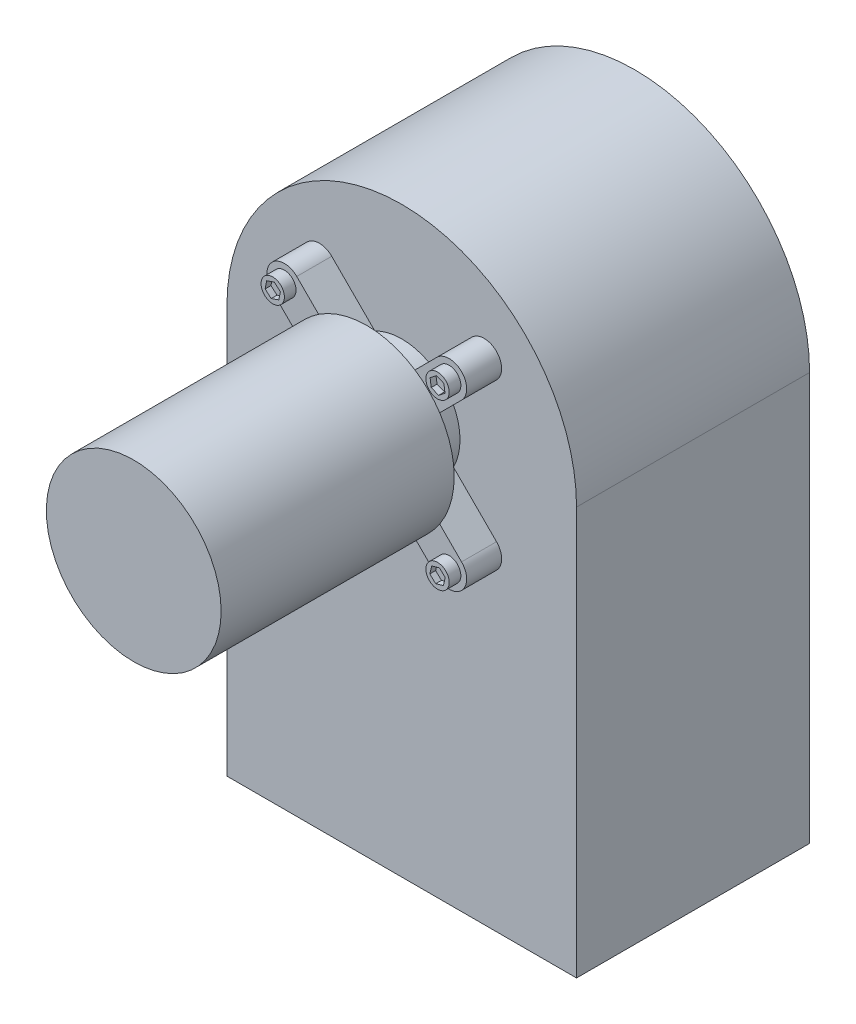
SolidWorks part; units mm, degrees
ref_plane "Front Plane" through (0, 0, 0) normal (0, 0, 1) x (1, 0, 0)
ref_plane "Top Plane" through (0, 0, 0) normal (0, 1, 0) x (1, 0, 0)
ref_plane "Right Plane" through (0, 0, 0) normal (1, 0, 0) x (0, 0, -1)
sketch "Sketch1" plane through (0, 0, 0) normal (0, 0, 1) x (1, 0, 0)
  line L1 (-15, 0) -> (15, 0)
  line L2 (-15, 0) -> (-15, -35)
  line L3 (-15, -35) -> (15, -35)
  line L4 (15, 0) -> (15, -35)
  line L5 (-15, 0) -> (15, -35) construction
  line L6 (-15, -35) -> (15, 0) construction
  circle A0 centre (0, 0) radius 15
  point P2 (0, -17.5)
  dimension "D1" = 30
  dimension "D2" = 35
extrude "Boss-Extrude1" add sketch "Sketch1" along normal blind 20 contours L1 A0 | L1 A0 | A0 L2 L3 L4
sketch "Sketch2" plane through (0, 0, 20) normal (0, 0, 1) x (1, 0, 0)
  circle A0 centre (0, 0) radius 4
  arc A1 (15, 0) -> (-15, 0) centre (0, 0) ccw construction
  dimension "D1" = 8
extrude "Cut-Extrude1" cut sketch "Sketch2" against normal through all both and the other way through all
sketch "Sketch4" plane through (0, 0, 20) normal (0, 0, 1) x (1, 0, 0)
  line L0 (7.0711, -7.0711) -> (-7.0711, 7.0711) construction
  line L1 (-7.0711, -7.0711) -> (7.0711, 7.0711) construction
  line L2 (15, 0) -> (15, -35) construction
  line L3 (8.1317, 6.0104) -> (-6.0104, -8.1317)
  line L4 (-8.1317, -6.0104) -> (6.0104, 8.1317)
  line L5 (6.0104, -8.1317) -> (-8.1317, 6.0104)
  line L6 (8.1317, -6.0104) -> (-6.0104, 8.1317)
  circle A0 centre (7.0711, -7.0711) radius 1.5
  circle A1 centre (-7.0711, -7.0711) radius 1.5
  circle A2 centre (7.0711, 7.0711) radius 1.5
  circle A3 centre (-7.0711, 7.0711) radius 1.5
  circle A4 centre (0, 0) radius 5
  point P12 (0, 0)
  point P20 (0, 0)
  circle M12 centre (0, 0) radius 4
  dimension "D4" = 3
  dimension "D5" = 10
  dimension "D1" = 90
  dimension "D2" = 45
  dimension "D3" = 20
extrude "Boss-Extrude2" add sketch "Sketch4" along normal blind 3 separate body contours A0 | A4 L5 A0 L6 | L6 A4 L3 M12 | L5 A4 L6 M12 | L3 A4 L5 M12 | L4 A4 L3 M12 | L5 A4 L4 M12 | L6 A4 L5 M12 | L4 A4 L6 M12 | L3 A4 L4 M12 | A4 L3 A2 L4 | A2 | A3 | A4 L6 A3 L5 | A4 L4 A1 L3 | A1
sketch "Sketch5" plane through (0, 0, 23) normal (0, 0, 1) x (1, 0, 0)
  circle A0 centre (7.0711, -7.0711) radius 1
  circle A1 centre (-7.0711, -7.0711) radius 1
  circle A2 centre (-7.0711, 7.0711) radius 1
  circle A3 centre (7.0711, 7.0711) radius 1
  arc A4 (6.0104, -8.1317) -> (8.1317, -6.0104) centre (7.0711, -7.0711) ccw construction
  arc A5 (-8.1317, -6.0104) -> (-6.0104, -8.1317) centre (-7.0711, -7.0711) ccw construction
  arc A6 (-6.0104, 8.1317) -> (-8.1317, 6.0104) centre (-7.0711, 7.0711) ccw construction
  arc A7 (8.1317, 6.0104) -> (6.0104, 8.1317) centre (7.0711, 7.0711) ccw construction
  dimension "D1" = 2
extrude "Boss-Extrude3" add sketch "Sketch5" along normal blind 1
sketch "Sketch6" plane through (0, 0, 24) normal (0, 0, 1) x (1, 0, 0)
  line L1 (7.2334, -6.4) -> (6.5711, -6.595)
  line L2 (6.5711, -6.595) -> (6.4088, -7.266)
  line L3 (6.4088, -7.266) -> (6.9088, -7.7421)
  line L4 (6.9088, -7.7421) -> (7.5711, -7.5471)
  line L5 (7.5711, -7.5471) -> (7.7334, -6.8761)
  line L6 (7.7334, -6.8761) -> (7.2334, -6.4)
  line L7 (-7.3172, -6.426) -> (-7.7528, -6.9617)
  line L8 (-7.7528, -6.9617) -> (-7.5066, -7.6067)
  line L9 (-7.5066, -7.6067) -> (-6.8249, -7.7161)
  line L10 (-6.8249, -7.7161) -> (-6.3894, -7.1804)
  line L11 (-6.3894, -7.1804) -> (-6.6355, -6.5354)
  line L12 (-6.6355, -6.5354) -> (-7.3172, -6.426)
  line L13 (-7.5907, 7.5256) -> (-7.7245, 6.8483)
  line L14 (-7.7245, 6.8483) -> (-7.2049, 6.3938)
  line L15 (-7.2049, 6.3938) -> (-6.5514, 6.6165)
  line L16 (-6.5514, 6.6165) -> (-6.4176, 7.2938)
  line L17 (-6.4176, 7.2938) -> (-6.9373, 7.7484)
  line L18 (-6.9373, 7.7484) -> (-7.5907, 7.5256)
  line L19 (6.975, 7.7548) -> (6.431, 7.3298)
  line L20 (6.431, 7.3298) -> (6.527, 6.6461)
  line L21 (6.527, 6.6461) -> (7.1671, 6.3874)
  line L22 (7.1671, 6.3874) -> (7.7112, 6.8124)
  line L23 (7.7112, 6.8124) -> (7.6151, 7.4961)
  line L24 (7.6151, 7.4961) -> (6.975, 7.7548)
  circle A0 centre (7.0711, -7.0711) radius 0.5979 construction
  circle A1 centre (-7.0711, -7.0711) radius 0.5979 construction
  circle A2 centre (-7.0711, 7.0711) radius 0.5979 construction
  circle A3 centre (7.0711, 7.0711) radius 0.5979 construction
  circle A4 centre (7.0711, 7.0711) radius 1 construction
  circle A5 centre (7.0711, -7.0711) radius 1 construction
  circle A6 centre (-7.0711, -7.0711) radius 1 construction
  circle A7 centre (-7.0711, 7.0711) radius 1 construction
  point P25 (0, 0)
  point P33 (0, 0)
  point P34 (0, 0)
  point P37 (0, 0)
  point P40 (0, 0)
  point P43 (0, 0)
  point P46 (0, 0)
  point P49 (0, 0)
  dimension "D1" = 0.5
extrude "Cut-Extrude2" cut sketch "Sketch6" against normal blind 0.5
sketch "Sketch7" plane through (0, 0, 23) normal (0, 0, 1) x (1, 0, 0)
  circle A0 centre (0, 0) radius 7.5
  circle A1 centre (0, 0) radius 4 construction
  point P2 (0, 0)
  dimension "D1" = 15
extrude "Boss-Extrude4" add sketch "Sketch7" along normal blind 20
